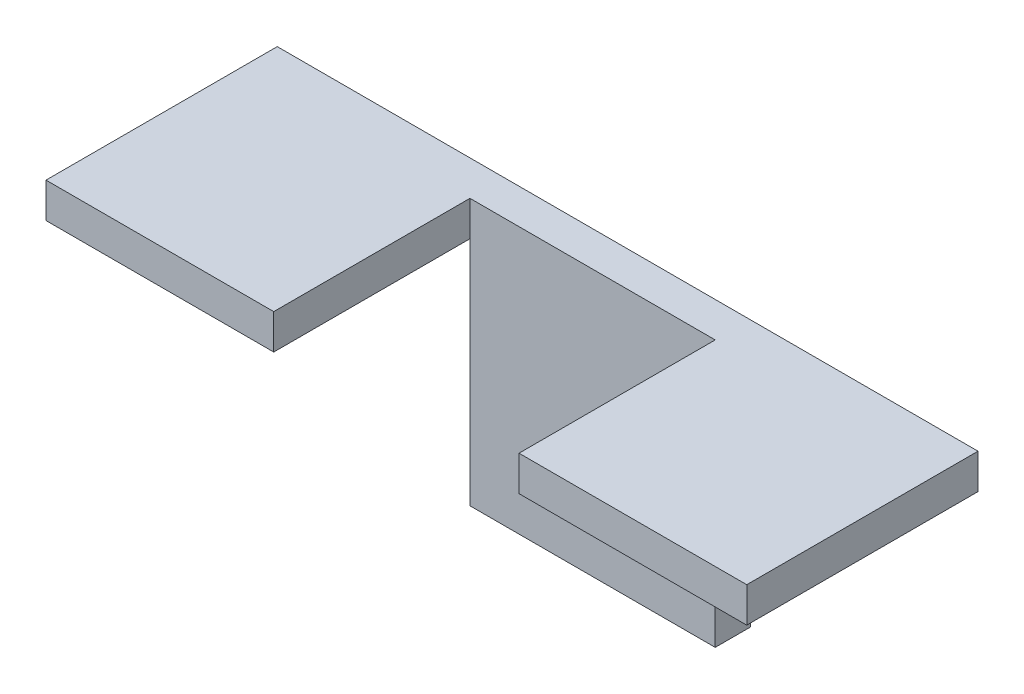
SolidWorks part; units mm, degrees
ref_plane "Front Plane" through (0, 0, 0) normal (0, 0, 1) x (1, 0, 0)
ref_plane "Top Plane" through (0, 0, 0) normal (0, 1, 0) x (1, 0, 0)
ref_plane "Right Plane" through (0, 0, 0) normal (1, 0, 0) x (0, 0, -1)
sketch "Sketch1" plane through (0, 0, 0) normal (0, 1, 0) x (1, 0, 0)
  line L1 (0, 0) -> (24.765, 0)
  line L2 (0, 0) -> (0, -25.146)
  line L3 (0, -25.146) -> (24.765, -25.146)
  line L4 (24.765, 0) -> (24.765, -25.146)
  line L5 (51.435, 0) -> (76.2, 0)
  line L6 (51.435, 0) -> (51.435, -25.146)
  line L7 (51.435, -25.146) -> (76.2, -25.146)
  line L8 (76.2, 0) -> (76.2, -25.146)
  dimension "D1" = 76.2
  dimension "D2" = 26.67
  dimension "D3" = 25.146
extrude "Boss-Extrude1" add sketch "Sketch1" along normal blind 3.81 contours L1 L4 L3 L2 | L5 L8 L7 L6
sketch "Sketch2" plane through (0, 3.81, 0) normal (0, 1, 0) x (1, 0, 0)
  line L0 (51.435, 0) -> (51.435, -25.146) construction
  line L1 (24.765, 0) -> (51.435, 0)
  line L2 (24.765, 0) -> (24.765, -3.81)
  line L3 (24.765, -3.81) -> (51.435, -3.81)
  line L4 (51.435, 0) -> (51.435, -3.81)
  dimension "D1" = 3.81
extrude "Boss-Extrude2" add sketch "Sketch2" against normal blind 28.956
